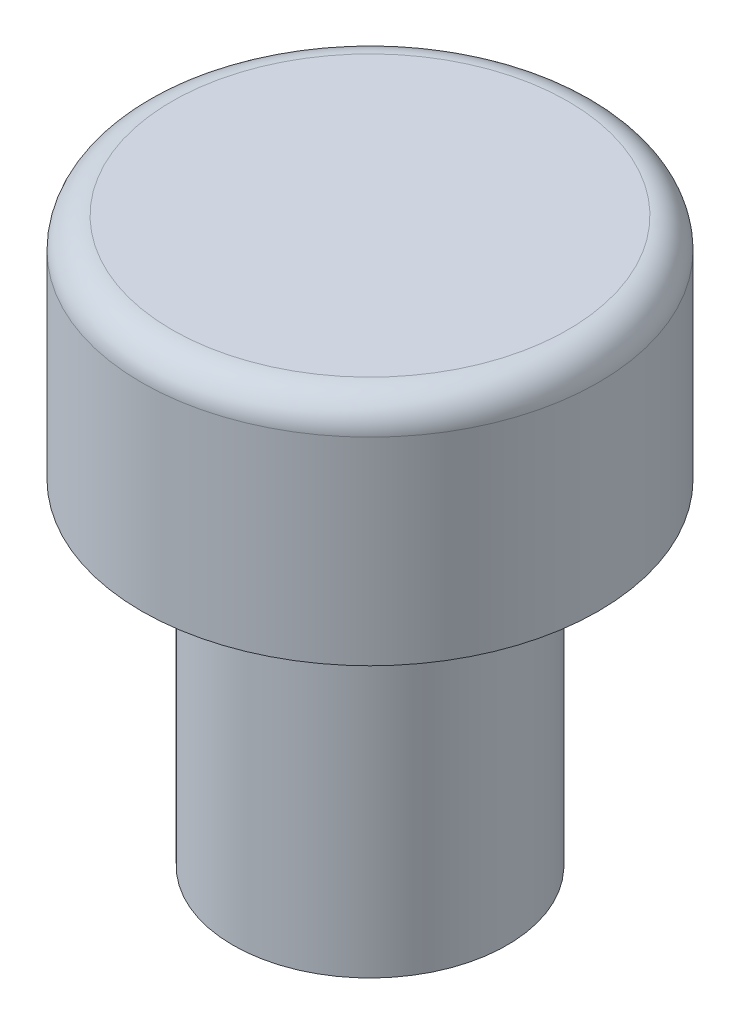
SolidWorks part; units mm, degrees
ref_plane "Front Plane" through (0, 0, 0) normal (0, 0, 1) x (1, 0, 0)
ref_plane "Top Plane" through (0, 0, 0) normal (0, 1, 0) x (1, 0, 0)
ref_plane "Right Plane" through (0, 0, 0) normal (1, 0, 0) x (0, 0, -1)
sketch "Sketch1" plane through (0, 0, 0) normal (0, 1, 0) x (1, 0, 0)
  circle A0 centre (0, 0) radius 7.5
  dimension "D1" = 15
extrude "Boss-Extrude1" add sketch "Sketch1" along normal blind 7.5
fillet "Fillet1" radius 1 1 edges at (0, 7.5, 7.5)
sketch "Sketch2" plane through (0, 0, 0) normal (0, -1, 0) x (1, 0, 0)
  circle A0 centre (0, 0) radius 4.5
  dimension "D1" = 9
extrude "Boss-Extrude2" add sketch "Sketch2" along normal blind 11
sketch "Sketch3" plane through (0, -11, 0) normal (0, -1, 0) x (-1, 0, 0)
  circle A0 centre (0, 0) radius 3.25
  dimension "D1" = 6.5
extrude "Cut-Extrude1" cut sketch "Sketch3" against normal blind 11
sketch "Sketch4" plane through (0, 0, 0) normal (0, -1, 0) x (-1, 0, 0)
  line L0 (1.75, -2.7386) -> (1.75, 2.7386)
  circle A0 centre (0, 0) radius 3.25 construction
  circle A1 centre (0, 0) radius 3.25
  circle M2 centre (0, 0) radius 3.25
  dimension "D1" = 1.75
  dimension "D2" = 6.5
extrude "Boss-Extrude3" add sketch "Sketch4" along normal blind 11 contours L0 M2
